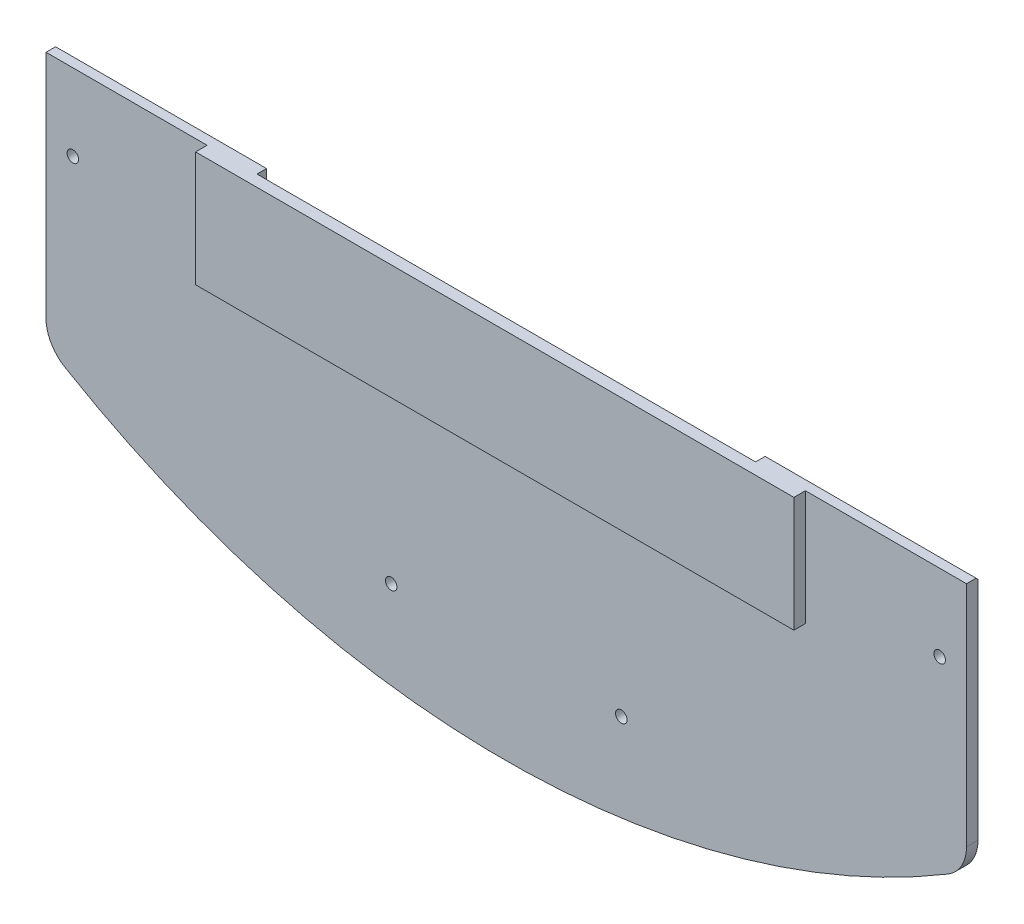
SolidWorks part; units mm, degrees
ref_plane "前视基准面" through (0, 0, 0) normal (0, 0, 1) x (1, 0, 0)
ref_plane "上视基准面" through (0, 0, 0) normal (0, 1, 0) x (1, 0, 0)
ref_plane "右视基准面" through (0, 0, 0) normal (1, 0, 0) x (0, 0, -1)
other "Configuration Table"
sketch "草图1" plane through (0, 0, 0) normal (0, 0, 1) x (1, 0, 0)
  line L1 (-120, -25) -> (120, -25)
  line L2 (-120, -25) -> (-120, -90.658)
  line L4 (120, -25) -> (120, -90)
  arc A1 (-120, -90.658) -> (120, -90) centre (-0.5219, 99.9986) ccw
  dimension "D1" = 65
  dimension "D3" = 25
  dimension "D5" = 450
  dimension "D2" = 240
  dimension "D4" = 120
  dimension "D6" = 100
extrude "凸台-拉伸1" add sketch "草图1" along normal blind 3
sketch "草图2" plane through (0, 0, 3) normal (0, 0, 1) x (1, 0, 0)
  line L0 (120, -25) -> (-120, -25) construction
  line L1 (-78, -25) -> (78, -25)
  line L2 (-78, -25) -> (-78, -55)
  line L3 (-78, -55) -> (78, -55)
  line L4 (78, -25) -> (78, -55)
  dimension "D1" = 156
  dimension "D2" = 78
  dimension "D3" = 30
extrude "凸台-拉伸2" add sketch "草图2" along normal blind 3
sketch "草图3" plane through (0, 0, 0) normal (0, 0, -1) x (-1, 0, 0)
  line L0 (0, 0) -> (0, -50000) construction
  line L1 (-120, -25) -> (120, -25) construction
  circle A0 centre (30, -100) radius 1.5
  circle A1 centre (113, -45) radius 1.5
  circle A2 centre (-113, -45) radius 1.5
  circle A3 centre (-30, -100) radius 1.5
  dimension "D1" = 30
  dimension "D2" = 3
  dimension "D4" = 3
  dimension "D3" = 75
  dimension "D5" = 113
  dimension "D6" = 20
extrude "切除-拉伸1" cut sketch "草图3" against normal blind 3
sketch "草图4" plane through (0, 0, 0) normal (0, 0, -1) x (-1, 0, 0)
  line L0 (-120, -25) -> (120, -25) construction
  line L1 (-65, -25) -> (65, -25)
  line L2 (-65, -25) -> (-65, -45)
  line L3 (-65, -45) -> (65, -45)
  line L4 (65, -25) -> (65, -45)
  dimension "D1" = 130
  dimension "D2" = 65
  dimension "D3" = 20
extrude "切除-拉伸2" cut sketch "草图4" against normal blind 3
fillet "圆角1" radius 10 2 edges at (120, -90, 1.5) (-120, -90.658, 1.5)
chamfer "倒角1" distance 0.5 angle 45 5 edges at (92.5, -25, 0) (-92.5, -25, 0) (-65, -35, 0) (65, -35, 0) (0, -45, 0)
